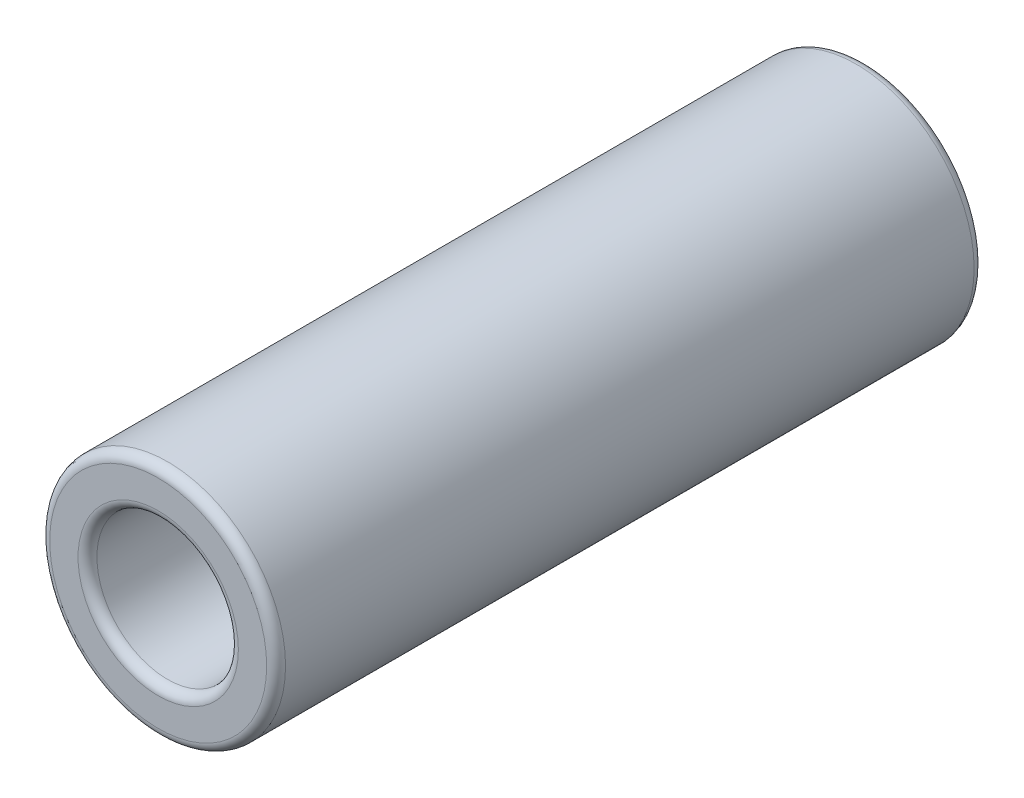
SolidWorks part; units mm, degrees
ref_plane "Front Plane" through (0, 0, 0) normal (0, 0, 1) x (1, 0, 0)
ref_plane "Top Plane" through (0, 0, 0) normal (0, 1, 0) x (1, 0, 0)
ref_plane "Right Plane" through (0, 0, 0) normal (1, 0, 0) x (0, 0, -1)
sketch "Sketch1" plane through (0, 0, 0) normal (0, 0, 1) x (1, 0, 0)
  circle A0 centre (0, 0) radius 2.5
  circle A1 centre (0, 0) radius 1.5
  dimension "D1" = 5
  dimension "D2" = 3
extrude "Boss-Extrude1" add sketch "Sketch1" along normal blind 15
fillet "Fillet1" radius 0.2 4 edges at (2.5, 0, 0) (1.5, 0, 0) (1.5, 0, 15) (2.5, 0, 15)
